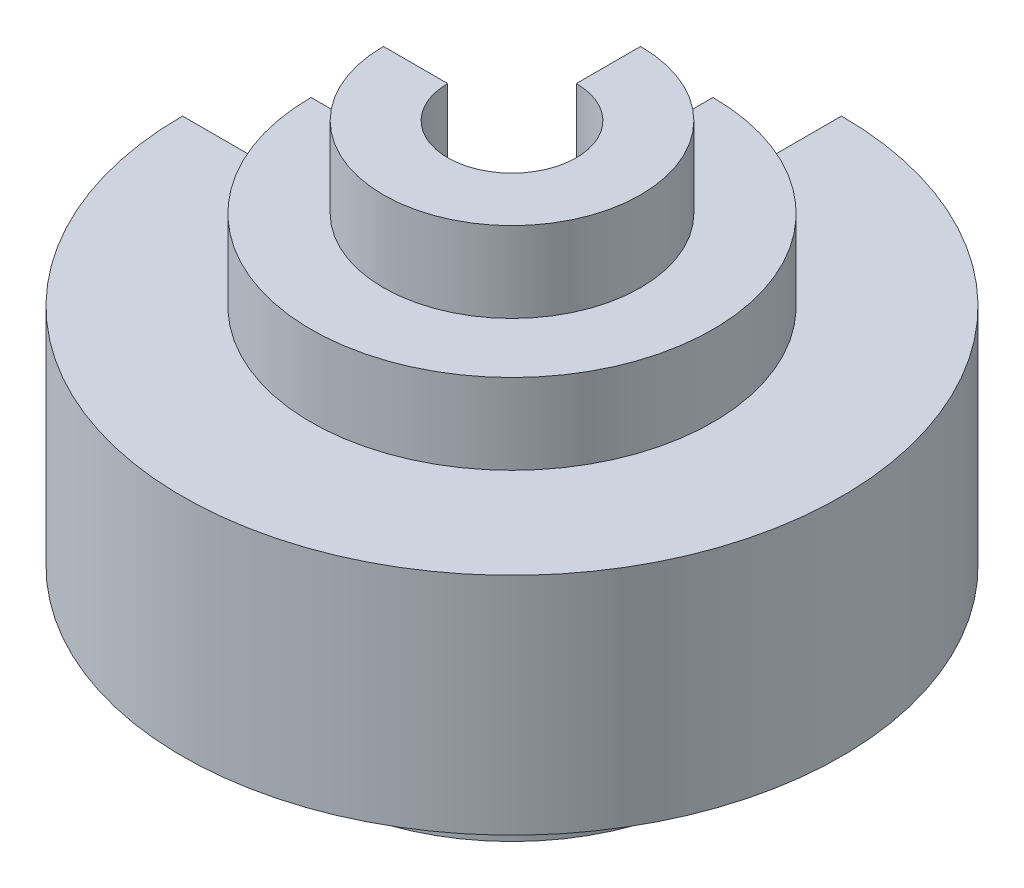
SolidWorks part; units mm, degrees
ref_plane "Front Plane" through (0, 0, 0) normal (0, 0, 1) x (1, 0, 0)
ref_plane "Top Plane" through (0, 0, 0) normal (0, 1, 0) x (1, 0, 0)
ref_plane "Right Plane" through (0, 0, 0) normal (1, 0, 0) x (0, 0, -1)
sketch "Sketch1" plane through (0, 0, 0) normal (0, 0, 1) x (1, 0, 0)
  line L0 (0, -107.2713) -> (0, 192.7287) construction
  line L1 (-40, 192.7287) -> (-80, 192.7287)
  line L2 (-80, 192.7287) -> (-80, 142.7287)
  line L3 (-80, 142.7287) -> (-125, 142.7287)
  line L4 (-125, 142.7287) -> (-125, 92.7287)
  line L5 (-125, 92.7287) -> (-205, 92.7287)
  line L6 (-205, 92.7287) -> (-205, -47.2713)
  line L7 (-205, -47.2713) -> (-125, -47.2713)
  line L8 (-125, -47.2713) -> (-125, -107.2713)
  line L9 (-125, -107.2713) -> (-60, -107.2713)
  line L10 (-60, -107.2713) -> (-60, -7.2713)
  line L11 (-60, -7.2713) -> (-155, -7.2713)
  line L12 (-155, -7.2713) -> (-155, 57.7287)
  line L13 (-155, 57.7287) -> (-75, 57.7287)
  line L14 (-75, 57.7287) -> (-75, 107.7287)
  line L15 (-75, 107.7287) -> (-40, 107.7287)
  line L16 (-40, 107.7287) -> (-40, 192.7287)
  point P16 (0, 0)
  dimension "D1" = 300
  dimension "D2" = 65
  dimension "D3" = 300
  dimension "D4" = 140
  dimension "D5" = 80
  dimension "D6" = 45
  dimension "D7" = 95
  dimension "D8" = 50
  dimension "D9" = 80
  dimension "D10" = 40
  dimension "D11" = 40
  dimension "D12" = 50
  dimension "D13" = 50
  dimension "D14" = 80
  dimension "D15" = 100
  dimension "D16" = 65
revolve "Revolve1" add sketch "Sketch1" angle 270 about L0
